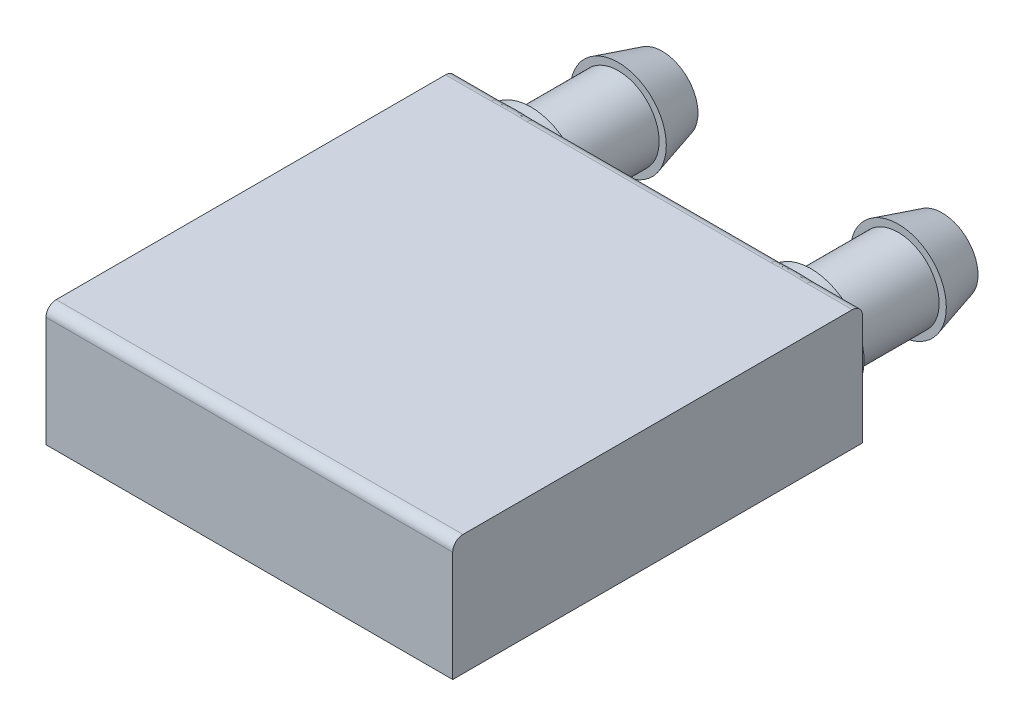
SolidWorks part; units mm, degrees
material "Plain Carbon Steel"
ref_plane "Front Plane" through (0, 0, 0) normal (0, 0, 1) x (1, 0, 0)
ref_plane "Top Plane" through (0, 0, 0) normal (0, 1, 0) x (1, 0, 0)
ref_plane "Right Plane" through (0, 0, 0) normal (1, 0, 0) x (0, 0, -1)
sketch "Sketch1" plane through (0, 0, 0) normal (0, 1, 0) x (1, 0, 0)
  line L1 (0, 0) -> (39.8, 0)
  line L2 (0, 0) -> (0, 40.1)
  line L3 (0, 40.1) -> (39.8, 40.1)
  line L4 (39.8, 0) -> (39.8, 40.1)
extrude "Boss-Extrude1" add sketch "Sketch1" along normal blind 11.8
sketch "Sketch2" plane through (0, 0, -40.1) normal (0, 0, -1) x (-1, 0, 0)
  line L0 (5.1841, 5.9) -> (-43.4873, 5.9) construction
  circle A0 centre (-6.2, 5.9) radius 5.2
  circle A1 centre (-33.6, 5.9) radius 5.2
extrude "Boss-Extrude2" add sketch "Sketch2" along normal blind 1.15
sketch "Sketch3" plane through (0, 0, -41.25) normal (0, 0, -1) x (-1, 0, 0)
  circle A0 centre (-33.6, 5.9) radius 4
  circle A1 centre (-6.2, 5.9) radius 4
extrude "Boss-Extrude3" add sketch "Sketch3" along normal blind 8.55
sketch "Sketch4" plane through (0, 0, -49.8) normal (0, 0, -1) x (-1, 0, 0)
  line L0 (-8.1851, 5.9) -> (-6.2, 5.9)
  line L1 (-6.2, 5.9) -> (-6.2, 4.3616)
  line L2 (-6.2, 4.3616) -> (-8.1851, 4.3616)
  line L3 (-8.1851, 4.3616) -> (-8.1851, 5.9)
sketch "Sketch5" plane through (0, 0, 0) normal (0, 1, 0) x (1, 0, 0)
  line L0 (6.2, 49.8) -> (6.2, 56.9697) construction
  line L1 (8.1851, 49.8) -> (6.2, 49.8) construction
  line L2 (6.2, 49.8) -> (10.9, 49.8)
  line L3 (10.9, 49.8) -> (9.7, 54.1)
  line L4 (9.7, 54.1) -> (6.2, 54.1)
  line L5 (6.2, 49.8) -> (6.2, 54.1)
extrude "Boss-Extrude4" add sketch "Sketch4" along normal blind 1
sketch "Sketch7" plane through (0, 5.9, 0) normal (0, 1, 0) x (1, 0, 0)
  line L0 (6.2, 49.8) -> (6.2, 56.9697) construction
  line L1 (6.2, 49.8) -> (10.9, 49.8)
  line L2 (10.9, 49.8) -> (9.7, 54.1)
  line L3 (9.7, 54.1) -> (6.2, 54.1)
  line L4 (6.2, 49.8) -> (6.2, 54.1)
revolve "Revolve2" add sketch "Sketch7" angle 360 about L0
sketch "Sketch10" plane through (0, 0, -49.8) normal (0, 0, -1) x (-1, 0, 0)
  line L0 (-33.6, 5.9) -> (-35.0503, 5.9)
  line L1 (-35.0503, 5.9) -> (-35.0503, 4.9326)
  line L2 (-35.0503, 4.9326) -> (-33.6, 4.9326)
  line L3 (-33.6, 4.9326) -> (-33.6, 5.9)
extrude "Boss-Extrude5" add sketch "Sketch10" along normal blind 1
sketch "Sketch11" plane through (0, 5.9, 0) normal (0, 1, 0) x (1, 0, 0)
  line L0 (33.6, 49.8) -> (33.6, 62.6491) construction
  line L1 (33.6, 49.8) -> (28.9, 49.8)
  line L2 (33.6, 49.8) -> (33.6, 54.1)
  line L3 (33.6, 54.1) -> (30.1, 54.1)
  line L4 (30.1, 54.1) -> (28.9, 49.8)
revolve "Revolve4" add sketch "Sketch11" angle 360 about L0
sketch "Sketch12" plane through (0, 0, -54.1) normal (0, 0, -1) x (-1, 0, 0)
  circle A0 centre (-6.2, 5.9) radius 3.15
  circle A1 centre (-33.6, 5.9) radius 3.15
extrude "Cut-Extrude1" cut sketch "Sketch12" against normal blind 15
fillet "Fillet1" radius 1 2 edges at (19.9, 11.8, 0) (19.9, 11.8, -40.1)
ref_plane "Plane1" through (19.9, 0, 0) normal (-1, 0, 0) x (0, 0, 1)
ref_plane "Plane2" through (0, 0, -20.05) normal (0, 0, 1) x (1, 0, 0)
